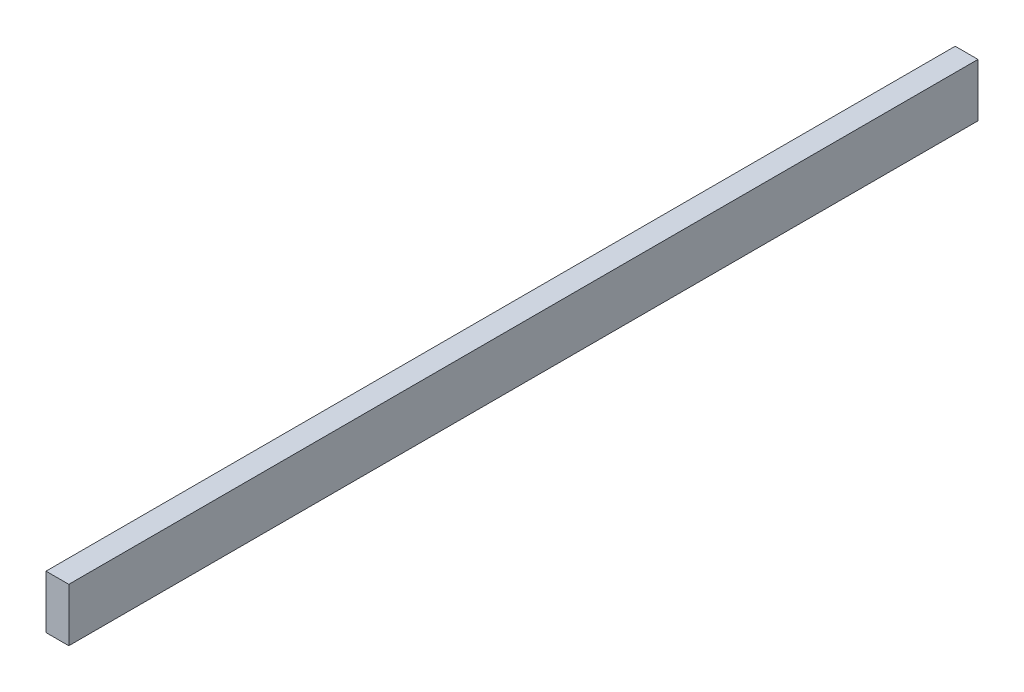
SolidWorks part; units mm, degrees
material "SPF Select 2Btr Grade Lumber"
ref_plane "Front Plane" through (0, 0, 0) normal (0, 0, 1) x (1, 0, 0)
ref_plane "Top Plane" through (0, 0, 0) normal (0, 1, 0) x (1, 0, 0)
ref_plane "Right Plane" through (0, 0, 0) normal (1, 0, 0) x (0, 0, -1)
sketch "Sketch1" plane through (0, 0, 0) normal (0, 0, 1) x (1, 0, 0)
  line L1 (0, 0) -> (38.1, 0)
  line L2 (0, 0) -> (0, 88.9)
  line L3 (0, 88.9) -> (38.1, 88.9)
  line L4 (38.1, 0) -> (38.1, 88.9)
  dimension "D1" = 38.1
  dimension "D2" = 88.9
extrude "Boss-Extrude1" add sketch "Sketch1" along normal blind 1518.68
